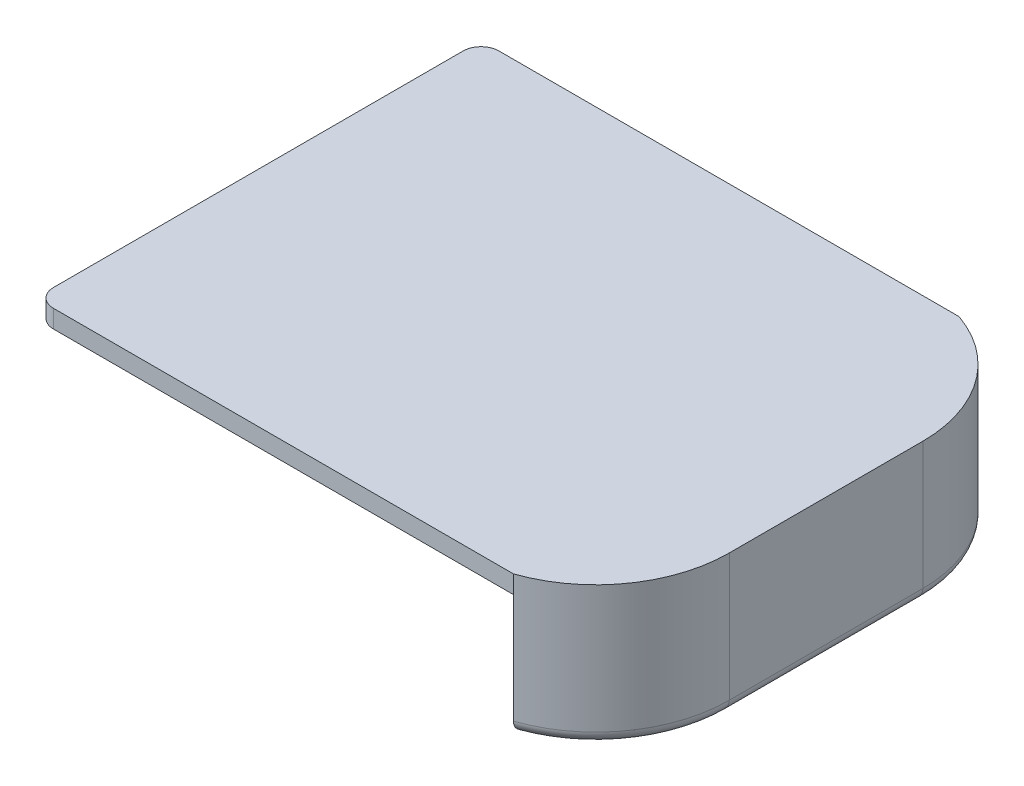
SolidWorks part; units mm, degrees
material "PLA"
ref_plane "Front Plane" through (0, 0, 0) normal (0, 0, 1) x (1, 0, 0)
ref_plane "Top Plane" through (0, 0, 0) normal (0, 1, 0) x (1, 0, 0)
ref_plane "Right Plane" through (0, 0, 0) normal (1, 0, 0) x (0, 0, -1)
sketch "Sketch1" plane through (0, 0, 0) normal (0, 1, 0) x (1, 0, 0)
  line L0 (1.0057, -6.715) -> (1.0057, 13.085)
  line L1 (1.0057, 13.085) -> (75.8057, 13.085)
  line L2 (1.0057, -6.715) -> (10.7057, -6.715)
  line L3 (10.7057, -6.715) -> (10.7057, 7.685)
  line L4 (10.7057, -13.515) -> (10.7057, 7.685)
  line L5 (30.7855, -6.715) -> (75.8057, -6.715)
  line L6 (75.8057, -6.715) -> (75.8057, 13.085)
  arc A0 (30.7855, -6.715) -> (10.7057, 7.685) centre (10.7057, -13.515) ccw
  arc A1 (10.7057, 7.685) -> (33.7057, -6.715) centre (10.7057, -17.8831) cw
  arc A2 (10.7057, 7.685) -> (33.7057, -6.715) centre (13.0157, -14.1934) cw
  dimension "D2" = 21.2
  dimension "D1" = 9.7
  dimension "D3" = 19.8
  dimension "D4" = 74.8
  dimension "D5" = 14.4
  dimension "D6" = 19.8
  dimension "D7" = 23
extrude "Boss-Extrude1" add sketch "Sketch1" along normal blind 15.3 contours A0 L5 L6 L1 L0 L2 L3
sketch "Sketch4" plane through (75.8057, 0, 0) normal (1, 0, 0) x (0, 0, -1)
  line L0 (-6.715, 4.35) -> (0.285, 4.35)
  line L1 (-6.715, 15.3) -> (-6.715, 0) construction
  line L2 (0.285, 4.35) -> (0.285, 10.25)
  line L3 (0.285, 10.25) -> (-6.715, 10.25)
  line L4 (-6.715, 10.25) -> (-6.715, 4.35)
  line L5 (-6.715, 0) -> (13.085, 0) construction
  dimension "D1" = 7
  dimension "D2" = 5.9
  dimension "D3" = 4.35
extrude "Cut-Extrude1" cut sketch "Sketch4" against normal through all
sketch "Sketch5" plane through (0, 15.3, 0) normal (0, 1, 0) x (1, 0, 0)
  line L1 (1.0057, 13.085) -> (75.8057, 13.085)
  line L2 (1.0057, 13.085) -> (1.0057, -6.715)
  line L3 (1.0057, -6.715) -> (75.8057, -6.715)
  line L4 (75.8057, 13.085) -> (75.8057, -6.715)
extrude "Boss-Extrude2" add sketch "Sketch5" along normal blind 2
sketch "Sketch6" plane through (0, 0, -13.085) normal (0, 0, -1) x (-1, 0, 0)
  line L0 (-75.8057, 17.3) -> (-75.8057, 20.3)
  line L1 (-1.0057, 17.3) -> (-1.0057, 20.3)
  line L2 (-1.0057, 20.3) -> (-75.8057, 20.3)
  line L3 (-75.8057, 17.3) -> (-1.0057, 17.3)
  dimension "D1" = 3
extrude "Boss-Extrude3" add sketch "Sketch6" against normal blind 37.2
sketch "Sketch7" plane through (1.0057, 0, 0) normal (-1, 0, 0) x (0, 0, 1)
  line L1 (24.115, 17.3) -> (-13.085, 17.3)
  line L2 (24.115, 17.3) -> (24.115, 20.3)
  line L3 (24.115, 20.3) -> (-13.085, 20.3)
  line L4 (-13.085, 17.3) -> (-13.085, 20.3)
extrude "Boss-Extrude4" add sketch "Sketch7" along normal blind 5
fillet "Fillet1" radius 3 1 edges at (-3.9943, 18.8, 24.115)
sketch "Sketch8" plane through (0, 20.3, 0) normal (0, 1, 0) x (1, 0, 0)
  line L0 (75.8057, 13.085) -> (90.8057, 13.085)
  line L1 (90.8057, 13.085) -> (90.8057, -3.0727)
  line L2 (75.8057, 13.085) -> (75.8057, -24.115)
  arc A0 (90.8057, -3.0727) -> (75.8057, -24.115) centre (68.5463, -3.0727) cw
  dimension "D1" = 15
  dimension "D2" = 16.1576
extrude "Boss-Extrude5" add sketch "Sketch8" against normal blind 23.3
fillet "Fillet2" radius 2 2 edges at (90.8057, -3, -5.0062) (86.6718, -3, 15.9934)
sketch "Sketch10" plane through (0, 0, 0) normal (0, -1, 0) x (-1, 0, 0)
  line L1 (-1.0057, -6.715) -> (-75.8057, -6.715)
  line L2 (-1.0057, -6.715) -> (-1.0057, 13.085)
  line L3 (-1.0057, 13.085) -> (-75.8057, 13.085)
  line L4 (-75.8057, -6.715) -> (-75.8057, 13.085)
extrude "Cut-Extrude2" cut sketch "Sketch10" against normal blind 0.2
sketch "Sketch11" plane through (0, -3, 0) normal (0, -1, 0) x (-1, 0, 0)
  line L0 (-75.8057, 13.085) -> (-75.8057, 3.085)
  line L1 (-75.8057, 13.085) -> (-75.8057, -21.9868) construction
  line L2 (-75.8057, 13.085) -> (-83.3057, 13.085)
  line L3 (-88.8057, 13.085) -> (-75.8057, 13.085) construction
  line L4 (-83.3057, 13.085) -> (-83.3057, 8.085)
  arc A1 (-75.8057, 3.085) -> (-83.3057, 8.085) centre (-75.8057, 11.21) cw
  dimension "D1" = 10
  dimension "D2" = 7.5
  dimension "D3" = 5
extrude "Cut-Extrude3" cut sketch "Sketch11" against normal blind 5 draft 30 draft outward yes
sketch "Sketch14" plane through (0, 0, -13.085) normal (0, 0, -1) x (-1, 0, 0)
  line L0 (-72.9189, 2) -> (-73.9582, 0.2)
  line L1 (-73.9582, 0.2) -> (-75.8057, 0.2)
  line L2 (-75.8057, 0.2) -> (-75.8057, 2)
  line L3 (-86.1924, 2) -> (-72.9189, 2) construction
  line L4 (-75.8057, 2) -> (-72.9189, 2)
extrude "Boss-Extrude6" add sketch "Sketch14" against normal blind 15
mirror "Mirror1" about plane through (0, 15.3, -13.085) normal (0, 0, -1) of bodies 111
